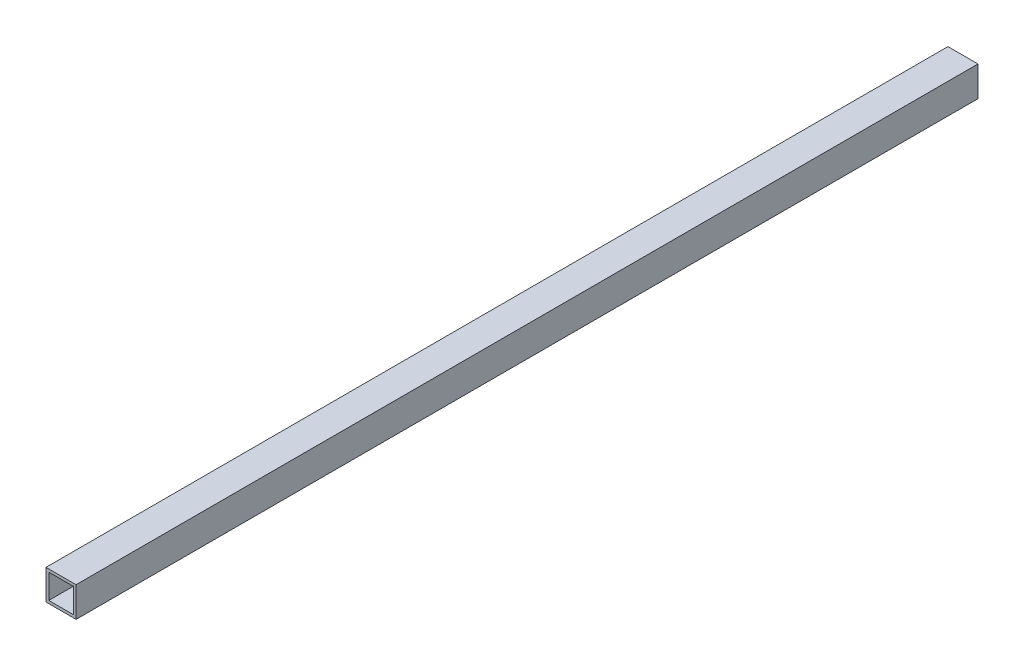
SolidWorks part; units mm, degrees
ref_plane "Front Plane" through (0, 0, 0) normal (0, 0, 1) x (1, 0, 0)
ref_plane "Top Plane" through (0, 0, 0) normal (0, 1, 0) x (1, 0, 0)
ref_plane "Right Plane" through (0, 0, 0) normal (1, 0, 0) x (0, 0, -1)
sketch "Sketch1" plane through (0, 0, 0) normal (0, 0, 1) x (1, 0, 0)
  line L1 (-5, 5) -> (5, 5)
  line L2 (-5, 5) -> (-5, -5)
  line L3 (-5, -5) -> (5, -5)
  line L4 (5, 5) -> (5, -5)
  line L5 (-5, 5) -> (5, -5) construction
  line L6 (-5, -5) -> (5, 5) construction
  line L7 (-4.0834, 4.0834) -> (4.0834, 4.0834)
  line L8 (-4.0834, 4.0834) -> (-4.0834, -4.0834)
  line L9 (-4.0834, -4.0834) -> (4.0834, -4.0834)
  line L10 (4.0834, 4.0834) -> (4.0834, -4.0834)
  line L11 (-4.0834, 4.0834) -> (4.0834, -4.0834) construction
  line L12 (-4.0834, -4.0834) -> (4.0834, 4.0834) construction
  point P0 (0, 0)
  point P6 (0, 0)
  dimension "D1" = 10
  dimension "D2" = 10
  dimension "D3" = 8.1669
extrude "Boss-Extrude1" add sketch "Sketch1" along normal blind 300
